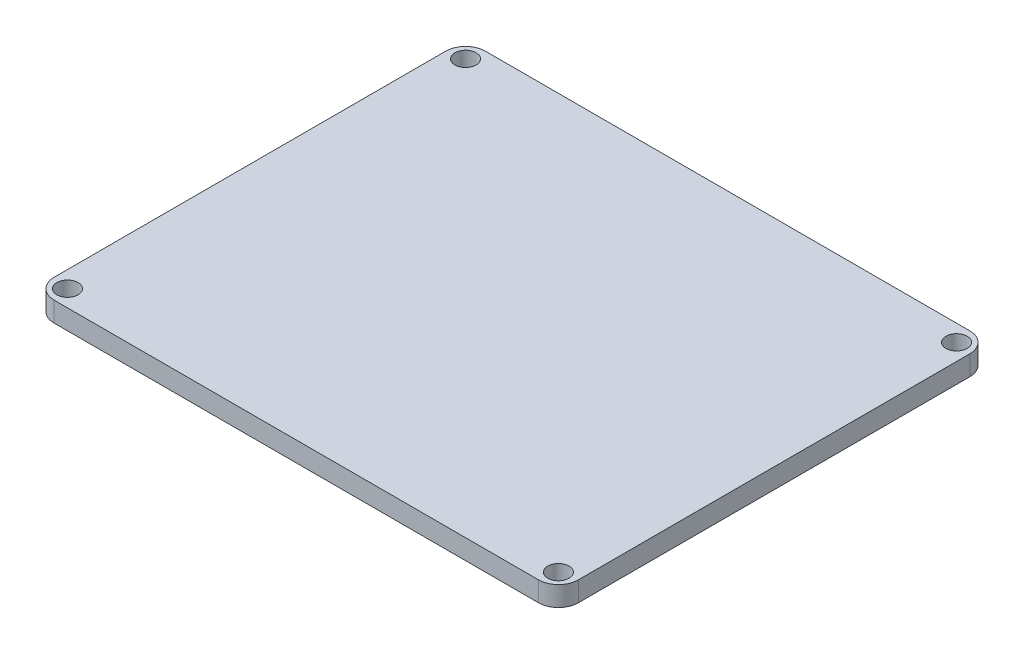
SolidWorks part; units mm, degrees
ref_plane "前视基准面" through (0, 0, 0) normal (0, 0, 1) x (1, 0, 0)
ref_plane "上视基准面" through (0, 0, 0) normal (0, 1, 0) x (1, 0, 0)
ref_plane "右视基准面" through (0, 0, 0) normal (1, 0, 0) x (0, 0, -1)
other "Configuration Table"
sketch "草图2" plane through (0, 0, 0) normal (0, 1, 0) x (1, 0, 0)
  line L1 (0, 0) -> (74, 0) construction
  line L2 (0, 0) -> (0, 60) construction
  line L3 (0, 60) -> (74, 60) construction
  line L4 (74, 0) -> (74, 60) construction
  line L5 (76.5, -2.5) -> (-2.5, -2.5)
  line L6 (76.5, -2.5) -> (76.5, 62.5)
  line L7 (76.5, 62.5) -> (-2.5, 62.5)
  line L8 (-2.5, -2.5) -> (-2.5, 62.5)
  line L9 (76.5, -2.5) -> (-2.5, 62.5) construction
  line L10 (76.5, 62.5) -> (-2.5, -2.5) construction
  circle A0 centre (0, 60) radius 1.6
  circle A1 centre (74, 60) radius 1.6
  circle A2 centre (74, 0) radius 1.6
  circle A3 centre (0, 0) radius 1.6
  point P4 (37, 30)
  point P5 (74, 30)
  point P7 (37, 60)
  point P8 (37, 30)
  dimension "D5" = 3.2
  dimension "D6" = 3.2
  dimension "D7" = 3.2
  dimension "D8" = 3.2
  dimension "D1" = 74
  dimension "D2" = 60
  dimension "D3" = 79
  dimension "D4" = 65
extrude "凸台-拉伸2" add sketch "草图2" along normal blind 3
fillet "圆角1" radius 3 4 edges at (76.5, 1.5, -62.5) (76.5, 1.5, 2.5) (-2.5, 1.5, 2.5) (-2.5, 1.5, -62.5)
